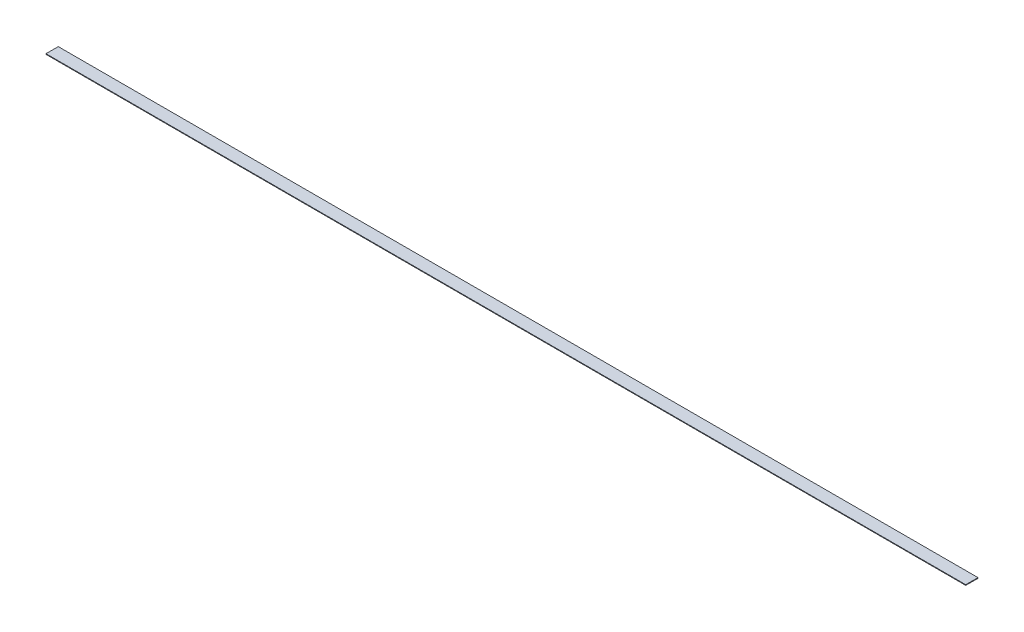
SolidWorks part; units mm, degrees
material "Резина"
ref_plane "Спереди" through (0, 0, 0) normal (0, 0, 1) x (1, 0, 0)
ref_plane "Сверху" through (0, 0, 0) normal (0, 1, 0) x (1, 0, 0)
ref_plane "Справа" through (0, 0, 0) normal (1, 0, 0) x (0, 0, -1)
sketch "Эскиз1" plane through (0, 0, 0) normal (0, 1, 0) x (1, 0, 0)
  line L0 (-1500, 0) -> (1500, 0) construction
  line L1 (-1500, 20) -> (1500, 20)
  line L2 (-1500, 20) -> (-1500, -20)
  line L3 (-1500, -20) -> (1500, -20)
  line L4 (1500, 20) -> (1500, -20)
  line L5 (-1500, 20) -> (1500, -20) construction
  line L6 (-1500, -20) -> (1500, 20) construction
  point P0 (0, 0)
  dimension "D1" = 3000
  dimension "D2" = 40
extrude "Бобышка-Вытянуть1" add sketch "Эскиз1" along normal blind 2
sketch "Эскиз2" plane through (0, 2, 0) normal (0, 1, 0) x (1, 0, 0)
  line L0 (1500, 0) -> (-1500, 0) construction
  line L1 (1500, -20) -> (1500, 20) construction
  line L2 (-1500, 20) -> (-1500, -20) construction
  circle A0 centre (1400, 0) radius 4.5
  circle A1 centre (1000, 0) radius 4.5
  circle A2 centre (600, 0) radius 4.5
  circle A3 centre (200, 0) radius 4.5
  circle A4 centre (-200, 0) radius 4.5
  circle A5 centre (-600, 0) radius 4.5
  circle A6 centre (-1000, 0) radius 4.5
  circle A7 centre (-1400, 0) radius 4.5
  dimension "D1" = 9
  dimension "D2" = 100
  dimension "D4" = 400
  dimension "D3" = 8
extrude "Вырез-Вытянуть1" [suppressed] cut sketch "Эскиз2" against normal through all
